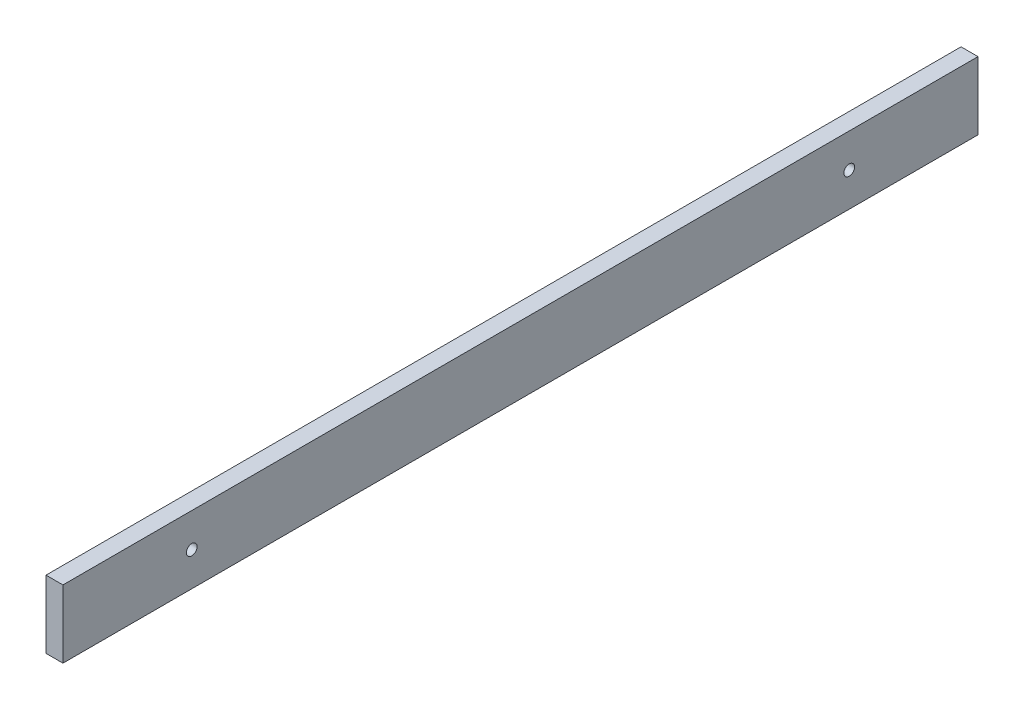
SolidWorks part; units mm, degrees
ref_plane "Alzado" through (0, 0, 0) normal (0, 0, 1) x (1, 0, 0)
ref_plane "Planta" through (0, 0, 0) normal (0, 1, 0) x (1, 0, 0)
ref_plane "Vista lateral" through (0, 0, 0) normal (1, 0, 0) x (0, 0, -1)
sketch "Croquis1" plane through (0, 0, 0) normal (1, 0, 0) x (0, 0, -1)
  line L1 (-135, -10) -> (135, -10)
  line L2 (-135, -10) -> (-135, 10)
  line L3 (-135, 10) -> (135, 10)
  line L4 (135, -10) -> (135, 10)
  line L5 (-135, -10) -> (135, 10) construction
  line L6 (-135, 10) -> (135, -10) construction
  circle A0 centre (97, 0) radius 1.58
  circle A1 centre (-97, 0) radius 1.58
  point P0 (0, 0)
  dimension "D3" = 3.16
  dimension "D5" = 3.16
  dimension "D1" = 270
  dimension "D2" = 20
  dimension "D4" = 38
  dimension "D6" = 38
extrude "Saliente-Extruir1" add sketch "Croquis1" along normal blind 5
